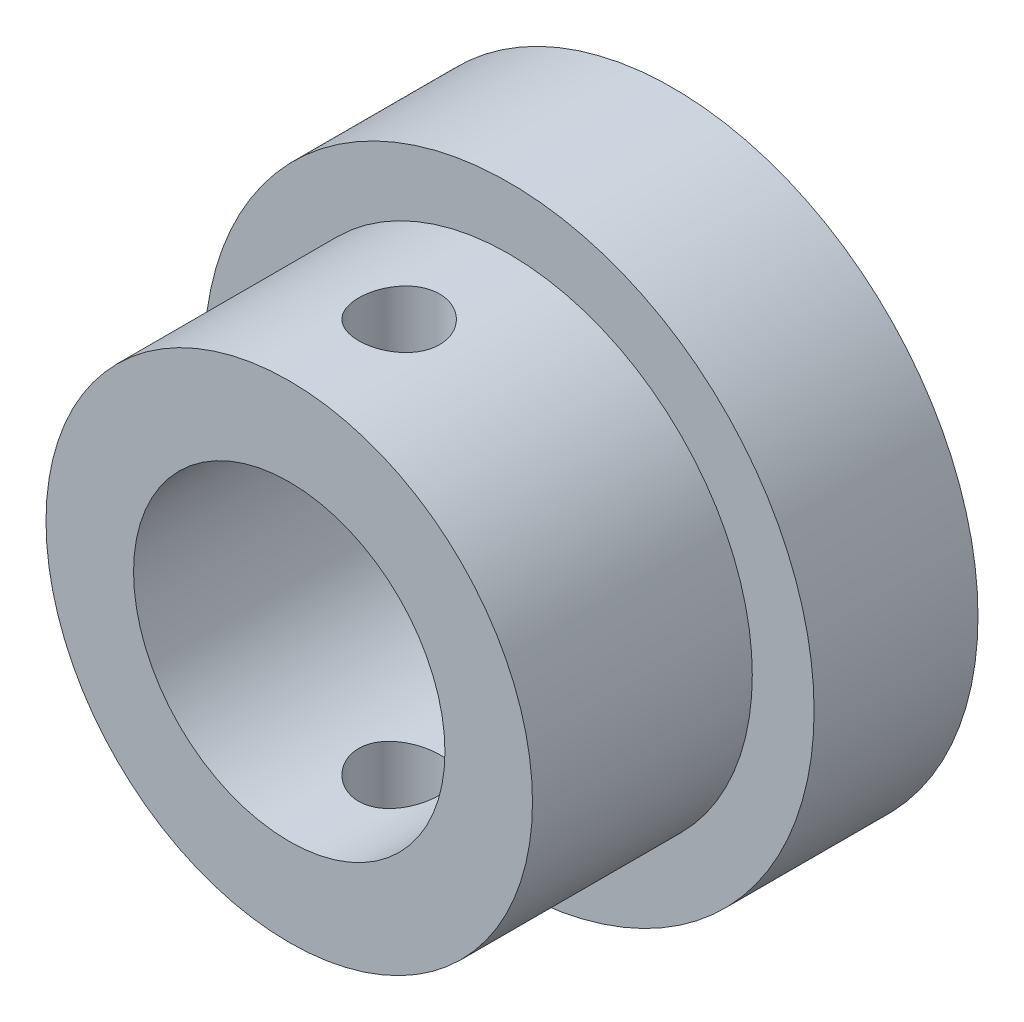
SolidWorks part; units mm, degrees
ref_plane "Front Plane" through (0, 0, 0) normal (1, 0, 0) x (0, 1, 0)
ref_plane "Top Plane" through (0, 0, 0) normal (0, 0, 1) x (0, 1, 0)
ref_plane "Right Plane" through (0, 0, 0) normal (0, 1, 0) x (-1, 0, 0)
sketch "Sketch1" plane through (0, 0, 0) normal (0, 0, 1) x (0, 1, 0)
  circle A0 centre (0, 0) radius 15.82
  dimension "D1" = 31.64
extrude "Boss-Extrude1" add sketch "Sketch1" along normal blind 8.5
sketch "Sketch2" plane through (0, 0, 8.5) normal (0, 0, 1) x (1, 0, 0)
  circle A0 centre (0, 0) radius 12.615
  dimension "D1" = 25.23
extrude "Boss-Extrude2" add sketch "Sketch2" along normal blind 11.4
sketch "Sketch3" plane through (0, 0, 19.9) normal (0, 0, 1) x (1, 0, 0)
  circle A0 centre (0, 0) radius 8.075
  dimension "D1" = 16.15
extrude "Cut-Extrude1" cut sketch "Sketch3" against normal through all
sketch "Sketch4" plane through (0, 0, 0) normal (0, 1, 0) x (-1, 0, 0)
  line L0 (0, 19.9) -> (0, 8.5) construction
  line L1 (12.615, 19.9) -> (-12.615, 19.9) construction
  line L2 (15.82, 8.5) -> (-15.82, 8.5) construction
  circle A0 centre (0, 14.2) radius 2.1
  dimension "D1" = 4.2
extrude "Cut-Extrude2" cut sketch "Sketch4" against normal through all both and the other way through all
